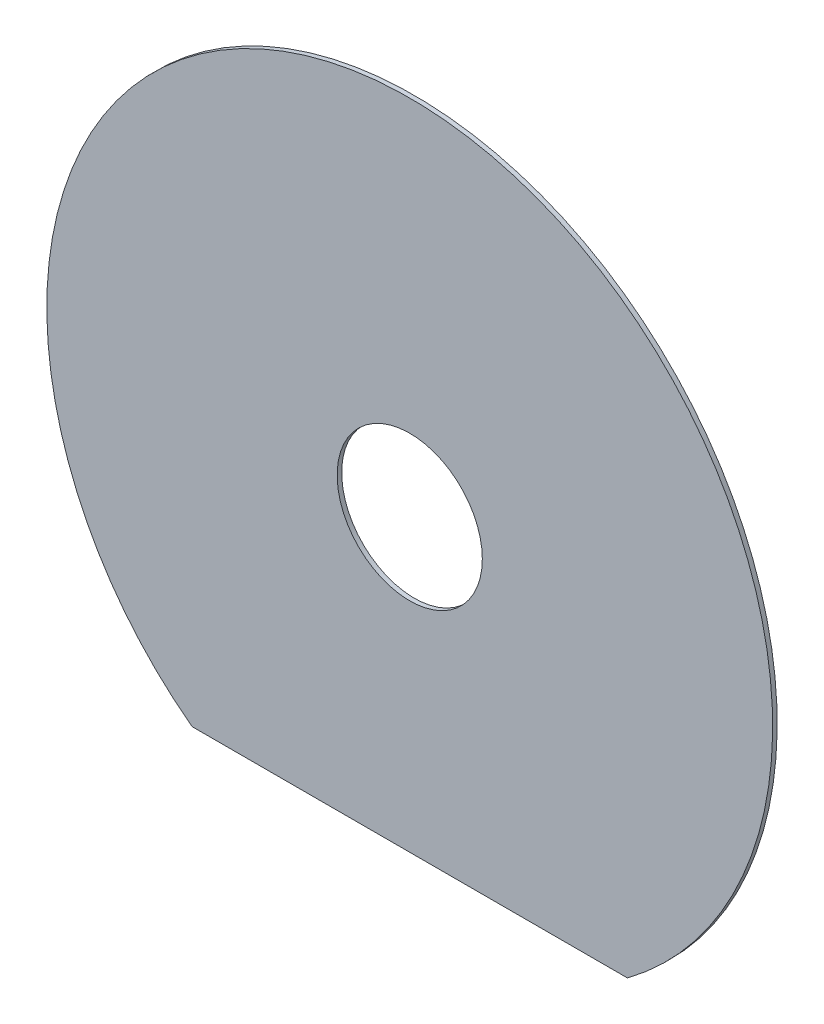
SolidWorks part; units mm, degrees
ref_plane "Front Plane" through (0, 0, 0) normal (0, 0, 1) x (1, 0, 0)
ref_plane "Top Plane" through (0, 0, 0) normal (0, 1, 0) x (1, 0, 0)
ref_plane "Right Plane" through (0, 0, 0) normal (1, 0, 0) x (0, 0, -1)
sketch "Sketch2" plane through (0, 0, 0) normal (0, 0, 1) x (1, 0, 0)
  line L0 (-152.4, -203.2) -> (152.4, -203.2)
  arc A0 (152.4, -203.2) -> (-152.4, -203.2) centre (0, 0) ccw
  circle A1 centre (0, 0) radius 50.8
  dimension "D1" = 304.8
extrude "Boss-Extrude1" add sketch "Sketch2" along normal blind 3.175
